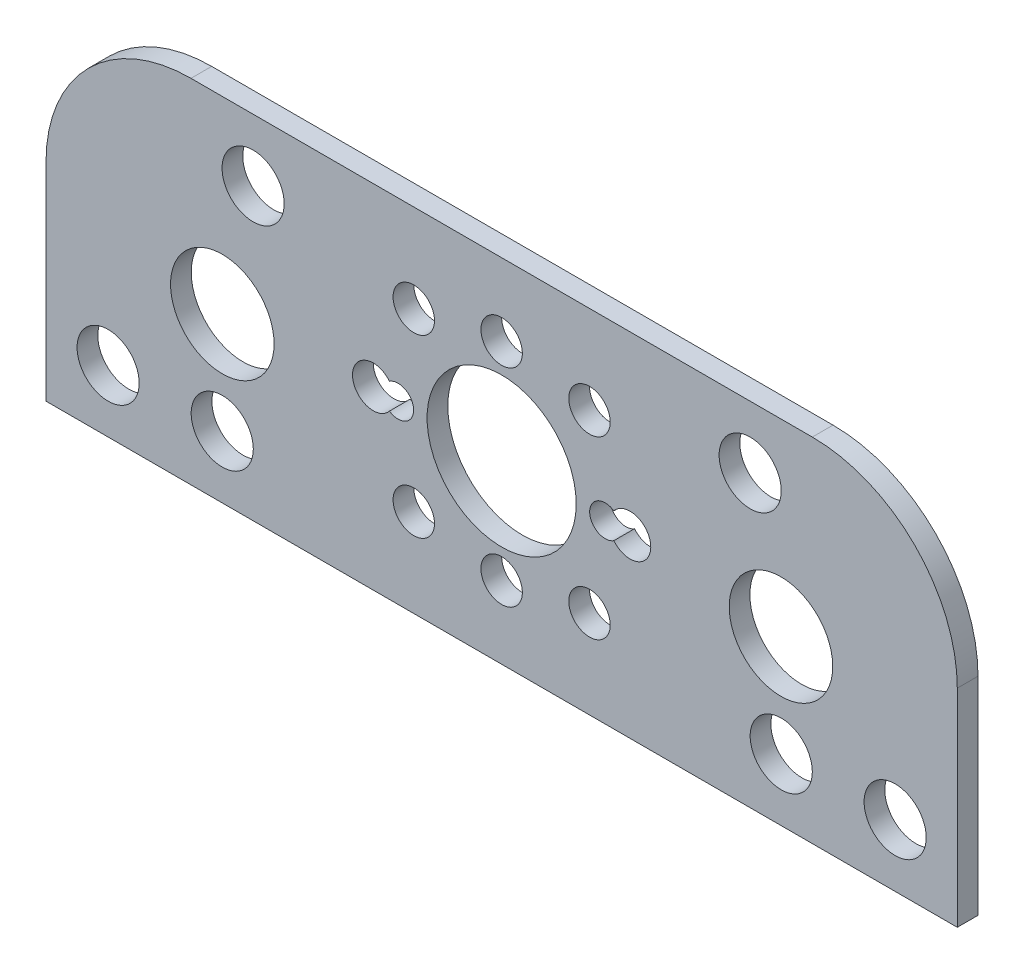
SolidWorks part; units mm, degrees
material "Thornel Mat VMA"
ref_plane "前视基准面" through (0, 0, 0) normal (0, 0, 1) x (1, 0, 0)
ref_plane "上视基准面" through (0, 0, 0) normal (0, 1, 0) x (1, 0, 0)
ref_plane "右视基准面" through (0, 0, 0) normal (1, 0, 0) x (0, 0, -1)
other "Configuration Table"
sketch "草图5" plane through (0, 0, 0) normal (0, 0, 1) x (1, 0, 0)
  circle A0 centre (0, 0) radius 8
sketch "草图6" plane through (0, 0, 0) normal (0, 0, 1) x (1, 0, 0)
  line L0 (-10.0496, 0) -> (9.8209, 0) construction
  line L1 (0, -6.8035) -> (0, 6.2826) construction
  line L2 (-4.2426, 4.2426) -> (0, 0) construction
  circle A0 centre (0, 0) radius 5 construction
  arc A1 (-5.4177, -0.6229) -> (-5.4177, 0.6229) centre (-5, 0) ccw
  arc A2 (5.4177, 0.6229) -> (5.4177, -0.6229) centre (5, 0) ccw
  circle A3 centre (0, 5) radius 1
  circle A4 centre (0, -5) radius 1
  arc A5 (-5.4177, 0.6229) -> (-5.4177, -0.6229) centre (-6.2, 0) ccw
  arc A6 (5.4177, -0.6229) -> (5.4177, 0.6229) centre (6.2, 0) ccw
  circle A7 centre (0, 0) radius 6 construction
  circle A8 centre (0, 0) radius 3.6
  circle A9 centre (-4.2426, 4.2426) radius 1
  circle A10 centre (4.2426, 4.2426) radius 1
  circle A11 centre (-4.2426, -4.2426) radius 1
  circle A12 centre (4.2426, -4.2426) radius 1
  circle A13 centre (0, 0) radius 4.25 construction
  dimension "D1" = 6.2
  dimension "D3" = 45
  dimension "D2" = 6.2
sketch "草图7" plane through (0, 0, 0) normal (0, 0, 1) x (1, 0, 0)
  circle A0 centre (0, 0) radius 13.5 construction
sketch "草图8" plane through (0, 0, 0) normal (0, 0, 1) x (1, 0, 0)
  circle A0 centre (-13.4867, -0.6) radius 2.5
  circle A1 centre (0, 0) radius 13.5 construction
  circle A2 centre (13.4867, -0.6) radius 2.5
  dimension "D1" = 0.6
  dimension "D2" = 0.6
sketch "草图10" plane through (0, 0, 0) normal (0, 0, 1) x (1, 0, 0)
  line L1 (-15, 8.5) -> (15, 8.5)
  line L2 (-22, 1.5) -> (-22, -8.5)
  line L3 (-22, -8.5) -> (22, -8.5)
  line L4 (22, 1.5) -> (22, -8.5)
  line L5 (-22, 8.5) -> (22, -8.5) construction
  line L6 (-22, -8.5) -> (22, 8.5) construction
  arc A0 (-22, 1.5) -> (-15, 8.5) centre (-15, 1.5) cw
  arc A1 (22, 1.5) -> (15, 8.5) centre (15, 1.5) ccw
  point P0 (0, 0)
  dimension "D4" = 7
  dimension "D5" = 7
  dimension "D1" = 17
  dimension "D2" = 44
extrude "凸台-拉伸1" add sketch "草图10" against normal blind 1
extrude "切除-拉伸1" cut sketch "草图6" against normal blind 2
extrude "切除-拉伸2" cut sketch "草图8" against normal blind 2
sketch "草图11" plane through (0, 0, 0) normal (0, 0, 1) x (1, 0, 0)
  line L1 (-22, -8.5) -> (-19, -8.5)
  line L2 (-22, -8.5) -> (-22, -5.5)
  line L3 (-22, -5.5) -> (-19, -5.5)
  line L4 (-19, -8.5) -> (-19, -5.5)
  line L5 (22, -8.5) -> (19, -8.5)
  line L6 (22, -8.5) -> (22, -5.5)
  line L7 (22, -5.5) -> (19, -5.5)
  line L8 (19, -8.5) -> (19, -5.5)
  dimension "D1" = 3
  dimension "D2" = 3
  dimension "D3" = 3
  dimension "D4" = 3
sketch "草图12" plane through (0, 0, 0) normal (0, 0, 1) x (1, 0, 0)
  line L0 (15, 8.5) -> (-15, 8.5) construction
  line L6 (15, 8.5) -> (-15, 8.5) construction
  circle A0 centre (-19, -5.5) radius 1.5
  circle A1 centre (19, -5.5) radius 1.5
  circle A2 centre (-12, 5.5) radius 1.5
  circle A3 centre (12, 5.5) radius 1.5
  circle A5 centre (-13.4907, -5.5) radius 1.5
  circle A6 centre (13.5, -5.5) radius 1.5
  point P20 (15, 8.5)
  point P52 (-15, 8.5)
  dimension "D1" = 3
  dimension "D2" = 3
  dimension "D3" = 3
  dimension "D4" = 3
extrude "切除-拉伸3" cut sketch "草图12" against normal blind 10
